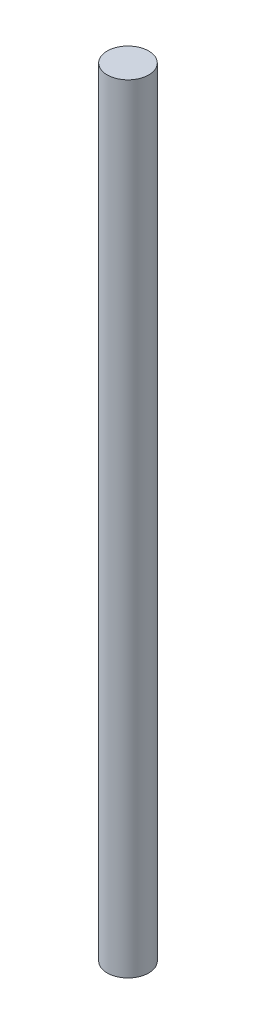
SolidWorks part; units mm, degrees
material "1023 Carbon Steel Sheet (SS)"
ref_plane "Front Plane" through (0, 0, 0) normal (0, 0, 1) x (1, 0, 0)
ref_plane "Top Plane" through (0, 0, 0) normal (0, 1, 0) x (1, 0, 0)
ref_plane "Right Plane" through (0, 0, 0) normal (1, 0, 0) x (0, 0, -1)
sketch "Sketch1" plane through (0, 0, 0) normal (0, 1, 0) x (1, 0, 0)
  circle A0 centre (0, 0) radius 4
  dimension "D1" = 8
extrude "Base" add sketch "Sketch1" along normal blind 150
